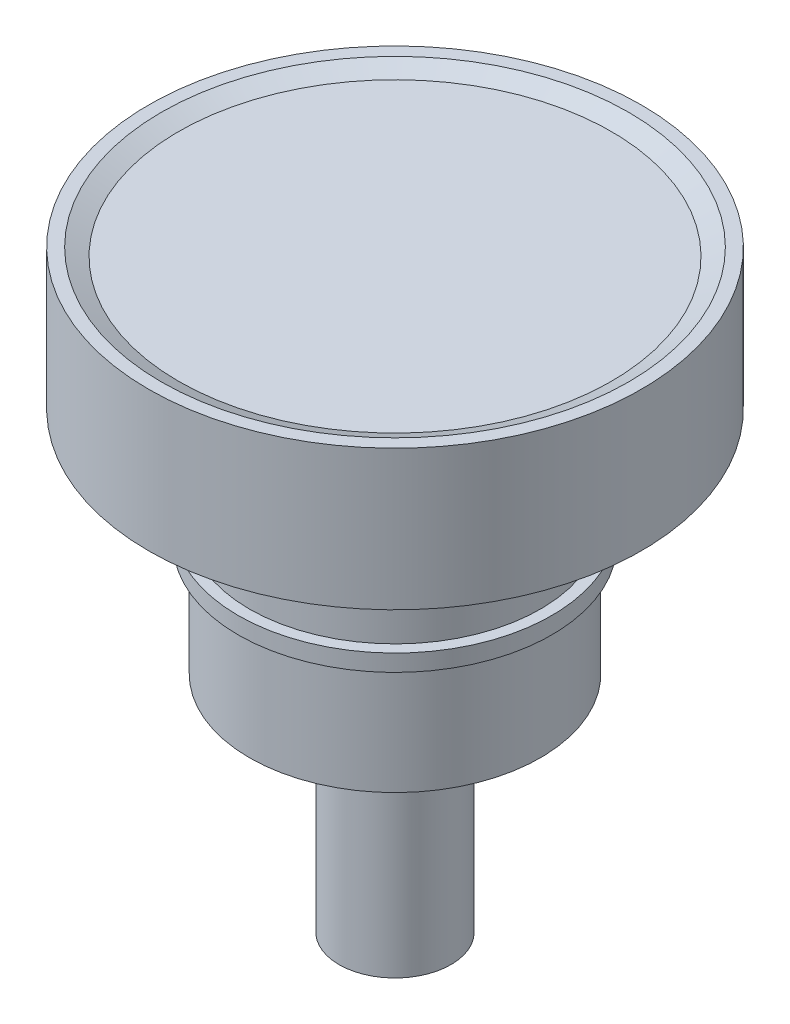
SolidWorks part; units mm, degrees
ref_plane "Front Plane" through (0, 0, 0) normal (0, 0, 1) x (1, 0, 0)
ref_plane "Top Plane" through (0, 0, 0) normal (0, 1, 0) x (1, 0, 0)
ref_plane "Right Plane" through (0, 0, 0) normal (1, 0, 0) x (0, 0, -1)
sketch "Sketch1" plane through (0, 0, 0) normal (0, 0, 1) x (1, 0, 0)
  line L0 (0, 0) -> (5, 0)
  line L1 (5, 0) -> (5, 20)
  line L2 (5, 20) -> (13, 20)
  line L3 (13, 20) -> (13, 30)
  line L4 (13, 30) -> (14, 30)
  line L5 (14, 30) -> (14, 31.5)
  line L6 (14, 31.5) -> (13, 31.5)
  line L7 (13, 31.5) -> (13, 40.5)
  line L8 (13, 40.5) -> (22, 40.5)
  line L9 (22, 40.5) -> (22, 53)
  line L12 (22, 53) -> (20.864, 53)
  line L13 (20.864, 53) -> (19.3258, 52.2793)
  line L14 (19.3258, 52.2793) -> (0, 52.2793)
  line L15 (0, 52.2793) -> (0, 0)
  dimension "D1" = 5
  dimension "D2" = 20
  dimension "D3" = 13
  dimension "D4" = 10
  dimension "D5" = 14
  dimension "D6" = 1.5
  dimension "D7" = 13
  dimension "D8" = 9
  dimension "D9" = 22
  dimension "D10" = 12.5
revolve "Revolve1" add sketch "Sketch1" angle 360 about L15
